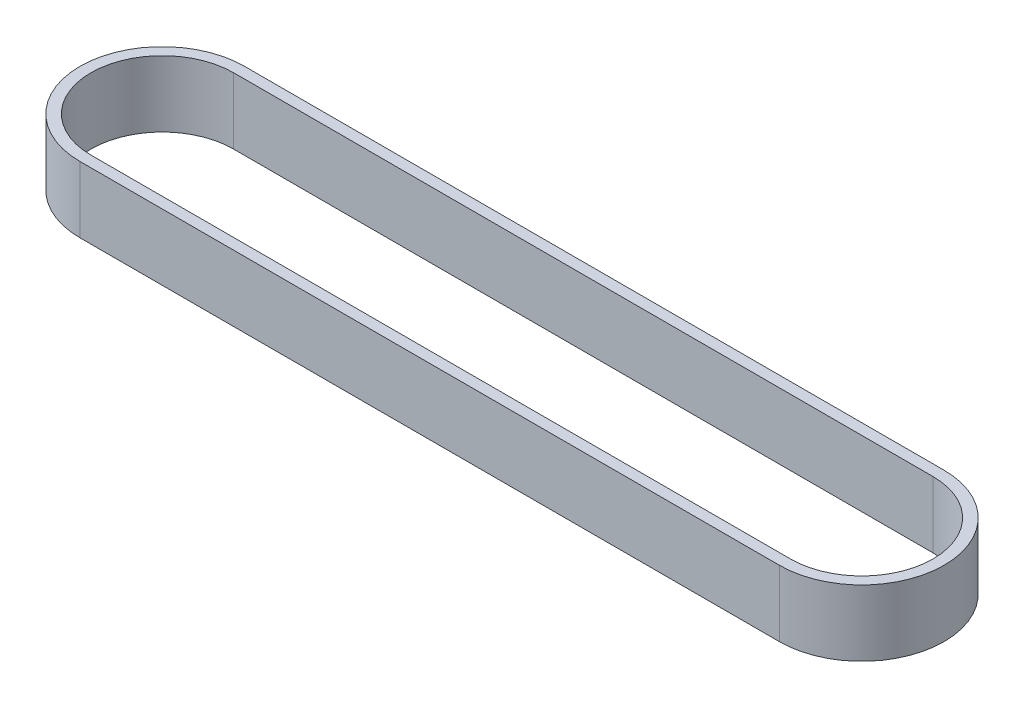
SolidWorks part; units mm, degrees
ref_plane "前视" through (0, 0, 0) normal (0, 0, 1) x (1, 0, 0)
ref_plane "上视" through (0, 0, 0) normal (0, 1, 0) x (1, 0, 0)
ref_plane "右视" through (0, 0, 0) normal (1, 0, 0) x (0, 0, -1)
sketch "草图1" plane through (0, 0, 0) normal (0, 1, 0) x (1, 0, 0)
  line L0 (-31.73, 7.47) -> (31.73, 7.47)
  line L1 (-31.73, 6.47) -> (31.73, 6.47)
  line L2 (-31.73, 6.47) -> (-31.73, -6.47) construction
  line L3 (-31.73, -6.47) -> (31.73, -6.47)
  line L4 (31.73, 6.47) -> (31.73, -6.47) construction
  line L5 (-31.73, 6.47) -> (31.73, -6.47) construction
  line L6 (-31.73, -6.47) -> (31.73, 6.47) construction
  line L7 (-31.73, -7.47) -> (31.73, -7.47)
  arc A0 (31.73, -6.47) -> (31.73, 6.47) centre (31.73, 0) ccw
  arc A1 (-31.73, 6.47) -> (-31.73, -6.47) centre (-31.73, 0) ccw
  arc A2 (31.73, -7.47) -> (31.73, 7.47) centre (31.73, 0) ccw
  arc A3 (-31.73, 7.47) -> (-31.73, -7.47) centre (-31.73, 0) ccw
  point P0 (0, 0)
  dimension "D1" = 12.94
  dimension "D2" = 63.46
  dimension "D3" = 1
extrude "凸台-拉伸1" add sketch "草图1" along normal blind 6
